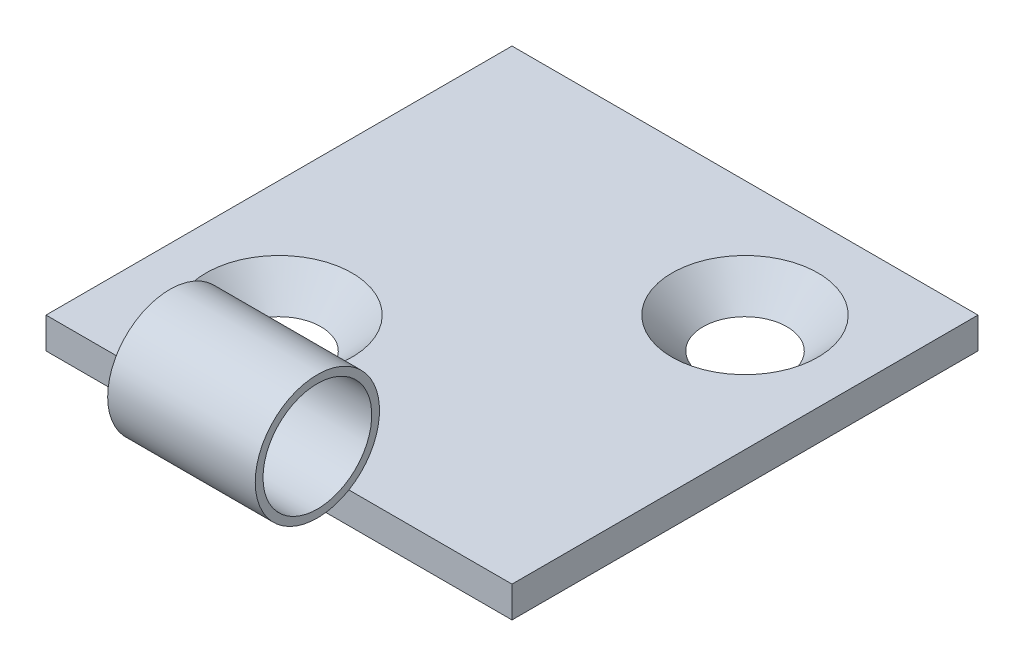
SolidWorks part; units mm, degrees
ref_plane "Front" through (0, 0, 0) normal (0, 0, 1) x (1, 0, 0)
ref_plane "Top" through (0, 0, 0) normal (0, 1, 0) x (1, 0, 0)
ref_plane "Right" through (0, 0, 0) normal (1, 0, 0) x (0, 0, -1)
sketch "Эскиз1" plane through (0, 0, 0) normal (0, 1, 0) x (1, 0, 0)
  line L1 (-85.0555, -0.1162) -> (-55.0555, -0.1162)
  line L2 (-85.0555, -0.1162) -> (-85.0555, -30.1162)
  line L3 (-85.0555, -30.1162) -> (-55.0555, -30.1162)
  line L4 (-55.0555, -0.1162) -> (-55.0555, -30.1162)
  dimension "D1" = 30
  dimension "D2" = 30
extrude "Бобышка-Вытянуть1" add sketch "Эскиз1" along normal blind 2
ref_plane "Плоскость1" through (-75.0555, 0, 0) normal (-1, 0, 0) x (0, 0, 1)
sketch "Эскиз2" plane through (-75.0555, 0, 0) normal (-1, 0, 0) x (0, 0, 1)
  line L1 (32.1462, 11.9708) -> (32.1462, -1.7274) construction
  line L2 (30.1162, 2) -> (30.1162, 0) construction
  circle A0 centre (32.1462, 5.4466) radius 4
  circle A3 centre (32.1462, 5.4466) radius 3.5
  dimension "D1" = 8
  dimension "D3" = 7
  dimension "D2" = 2.03
extrude "Бобышка-Вытянуть2" add sketch "Эскиз2" against normal blind 9.5 separate body
hole_wizard "Зенковка для  винта с плоской головкой M41" positions "Эскиз3" profile "Эскиз4" countersink size "M4" standard "Ansi Metric"
sketch "Эскиз3" plane through (0, 2, 0) normal (0, 1, 0) x (1, 0, 0)
  line L0 (-70.0555, -0.1162) -> (-70.0555, -36.4675) construction
  line L1 (-55.0555, -0.1162) -> (-85.0555, -0.1162) construction
  line L3 (-85.0555, -15.1162) -> (-55.0555, -15.1162)
  line L4 (-85.0555, -0.1162) -> (-85.0555, -30.1162) construction
  line L5 (-55.0555, -30.1162) -> (-55.0555, -0.1162) construction
  line L7 (-55.0555, -0.1162) -> (-70.0555, -15.1162) construction
  line L9 (-70.0555, -15.1162) -> (-85.0555, -30.1162) construction
  point P0 (-77.5555, -22.6162)
  point P2 (-62.5555, -7.6162)
  point P28 (0, 0)
  point P29 (-77.5555, -22.6162)
  point P30 (0, 0)
  point P31 (-62.5555, -7.6162)
sketch "Эскиз4" plane through (-77.5555, 2, 22.6162) normal (1, 0, 0) x (0, 0, 1)
  line L0 (0, 0) -> (0, 22.3519)
  line L1 (0, 22.3519) -> (2.25, 21)
  line L2 (2.25, 21) -> (2.25, 2.45)
  line L3 (2.25, 2.45) -> (4.7, 0)
  line L5 (4.7, 0) -> (0, 0)
  line L6 (-2.25, 2.45) -> (-4.7, 0) construction
  line L10 (0, 22.3519) -> (-2.25, 21) construction
  line L11 (0, -6.35) -> (0, 107.95) construction
  dimension "Диаметр отверстия" = 4.5
  dimension "Глубина отверстия" = 21
  dimension "Диаметр передней зенковки" = 9.4
  dimension "Угол передней зенковки" = 90
  dimension "Угол заточки сверла" = 118
